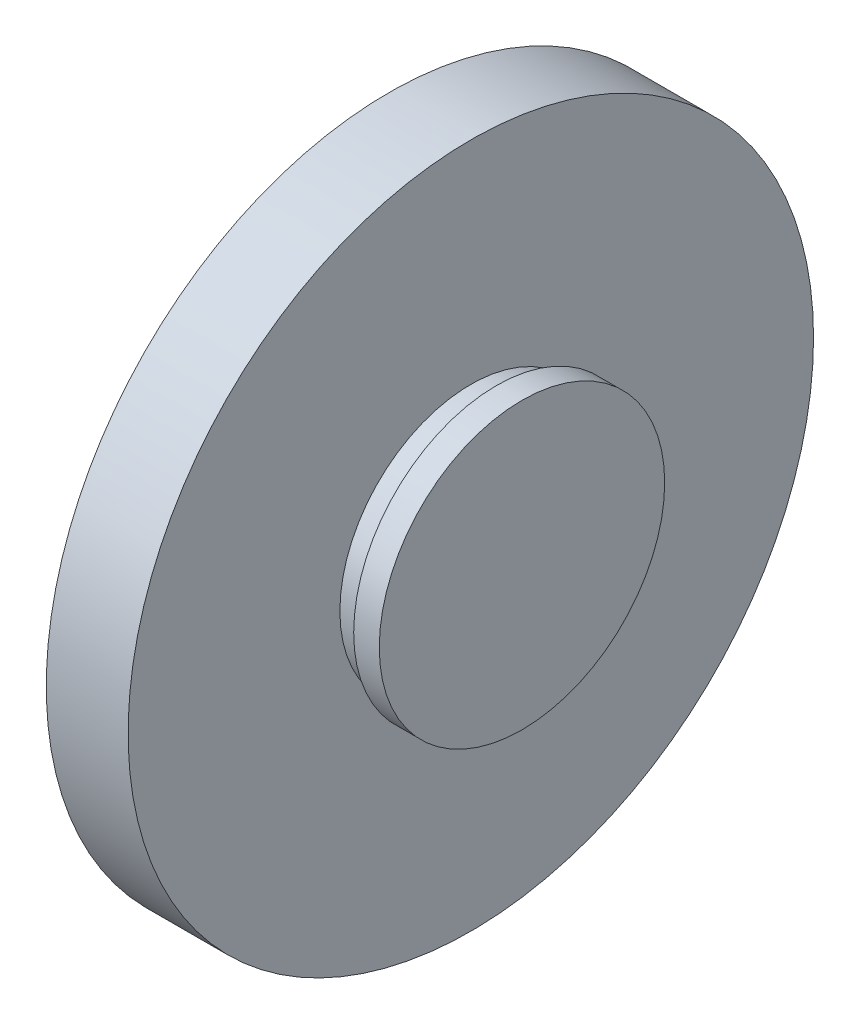
SolidWorks part; units mm, degrees
ref_plane "Front Plane" through (0, 0, 0) normal (0, 0, 1) x (1, 0, 0)
ref_plane "Top Plane" through (0, 0, 0) normal (0, 1, 0) x (1, 0, 0)
ref_plane "Right Plane" through (0, 0, 0) normal (1, 0, 0) x (0, 0, -1)
sketch "Sketch2" plane through (0, 0, 0) normal (1, 0, 0) x (0, 0, -1)
  circle A0 centre (0, 0) radius 17.9
  circle A1 centre (0, 0) radius 12.8
  circle A2 centre (0, 0) radius 33.5
  point P6 (0, 0)
  dimension "D1" = 35.8
  dimension "D2" = 25.6
  dimension "D3" = 67
extrude "Boss-Extrude1" add sketch "Sketch2" along normal blind 8 contours A2
sketch "Sketch7" plane through (8, 0, 0) normal (1, 0, 0) x (0, 0, -1)
  circle A0 centre (0, 0) radius 12.8
  dimension "D1" = 25.6
extrude "Boss-Extrude2" add sketch "Sketch7" along normal blind 2.5
sketch "Sketch8" plane through (10.5, 0, 0) normal (1, 0, 0) x (0, 0, -1)
  circle A0 centre (0, 0) radius 13.95
  dimension "D1" = 27.9
extrude "Boss-Extrude3" add sketch "Sketch8" along normal blind 2.5
sketch "Sketch10" plane through (0, 0, 0) normal (-1, 0, 0) x (0, 0, 1)
  line L0 (-4, -27.2039) -> (-6.5, -6.5)
  line L1 (-6.5, -6.5) -> (-27.2039, -4)
  line L2 (-27.2039, 4) -> (-6.5, 6.5)
  line L3 (-6.5, 6.5) -> (-4, 27.2039)
  line L4 (4, 27.2039) -> (6.5, 6.5)
  line L5 (6.5, 6.5) -> (27.2039, 4)
  line L6 (27.2039, -4) -> (6.5, -6.5)
  line L7 (6.5, -6.5) -> (4, -27.2039)
  line L8 (-6.5, 6.5) -> (6.5, 6.5) construction
  line L9 (6.5, 6.5) -> (6.5, -6.5) construction
  line L10 (6.5, -6.5) -> (-6.5, -6.5) construction
  line L11 (-6.5, 6.5) -> (-6.5, -6.5) construction
  line L12 (0, 0) -> (-6.5, 0) construction
  line L13 (0, 0) -> (0, -6.5) construction
  line L14 (-26.7209, 0) -> (-6.5, 0) construction
  line L15 (0, -26.7209) -> (0, -6.5) construction
  line L16 (26.7209, 0) -> (6.5, 0) construction
  line L17 (0, 6.5) -> (0, 26.7209) construction
  line L18 (-30.75, 0) -> (-26.7209, 0) construction
  line L19 (26.7209, 0) -> (30.75, 0) construction
  arc A0 (-27.2039, 4) -> (-27.2039, -4) centre (-26.7209, 0) ccw
  arc A1 (27.2039, 4) -> (27.2039, -4) centre (26.7209, 0) cw
  arc A2 (-4, 27.2039) -> (4, 27.2039) centre (0, 26.7209) cw
  arc A3 (4, -27.2039) -> (-4, -27.2039) centre (0, -26.7209) cw
  dimension "D1" = 61.5
  dimension "D2" = 13
  dimension "D3" = 8
extrude "Cut-Extrude1" cut sketch "Sketch10" against normal blind 5.5
sketch "Sketch11" plane through (5.5, 0, 0) normal (-1, 0, 0) x (0, 0, 1)
  circle A0 centre (0, 0) radius 6
  dimension "D1" = 12
extrude "Cut-Extrude2" cut sketch "Sketch11" against normal blind 3.2
